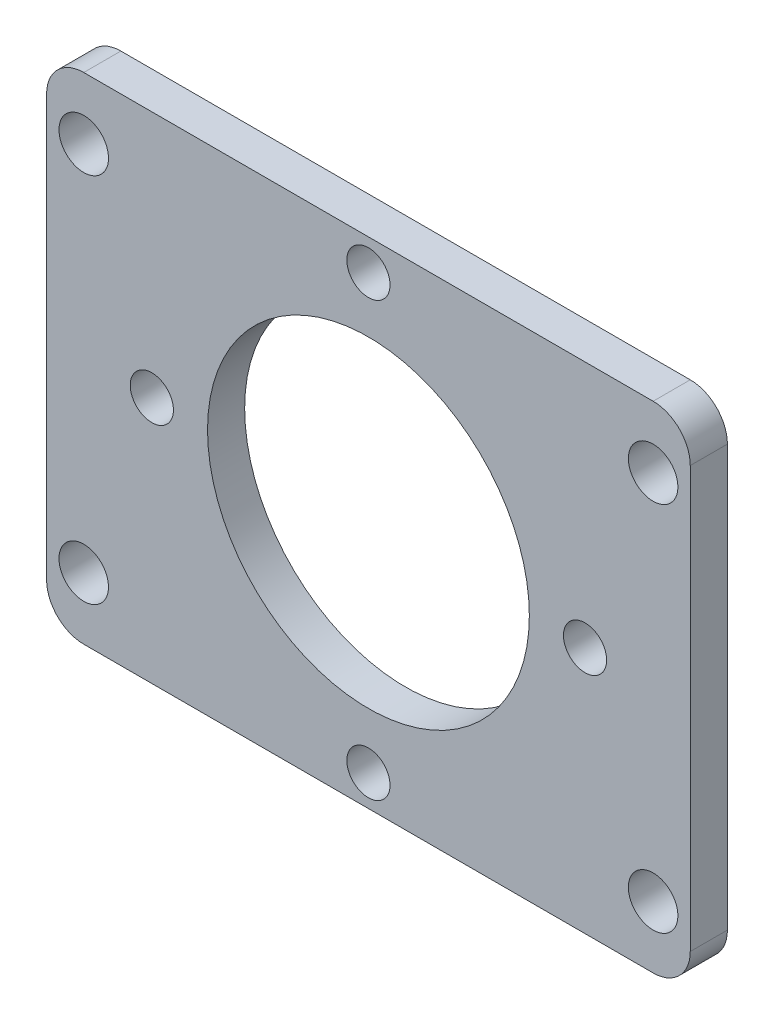
SolidWorks part; units mm, degrees
ref_plane "前视基准面" through (0, 0, 0) normal (0, 0, 1) x (1, 0, 0)
ref_plane "上视基准面" through (0, 0, 0) normal (0, 1, 0) x (1, 0, 0)
ref_plane "右视基准面" through (0, 0, 0) normal (1, 0, 0) x (0, 0, -1)
sketch "草图1" plane through (0, 0, 0) normal (0, 0, 1) x (1, 0, 0)
  line L0 (0, 26.4069) -> (0, -23.2494) construction
  line L1 (-26, 20) -> (26, 20)
  line L2 (-26, 20) -> (-26, -20)
  line L3 (-26, -20) -> (26, -20)
  line L4 (26, 20) -> (26, -20)
  line L5 (-29.1916, 0) -> (31.5892, 0) construction
  circle A0 centre (0, 0) radius 17.5 construction
  circle A1 centre (0, 0) radius 13
  circle A2 centre (0, 17.5) radius 1.7441
  circle A3 centre (17.5, 0) radius 1.7441
  circle A4 centre (0, -17.5) radius 1.7441
  circle A5 centre (-17.5, 0) radius 1.7441
  circle A6 centre (0, 0) radius 21 construction
  circle A7 centre (-23, 15) radius 2
  circle A8 centre (23, 15) radius 2
  circle A9 centre (23, -15) radius 2
  circle A10 centre (-23, -15) radius 2
  point P15 (0, 0)
  dimension "D1" = 20
  dimension "D5" = 23
  dimension "D6" = 15
  dimension "D2" = 20
  dimension "D3" = 26
  dimension "D4" = 26
extrude "凸台-拉伸1" add sketch "草图1" along normal blind 3
fillet "圆角1" radius 3 4 edges at (-26, -20, 1.5) (-26, 20, 1.5) (26, -20, 1.5) (26, 20, 1.5)
